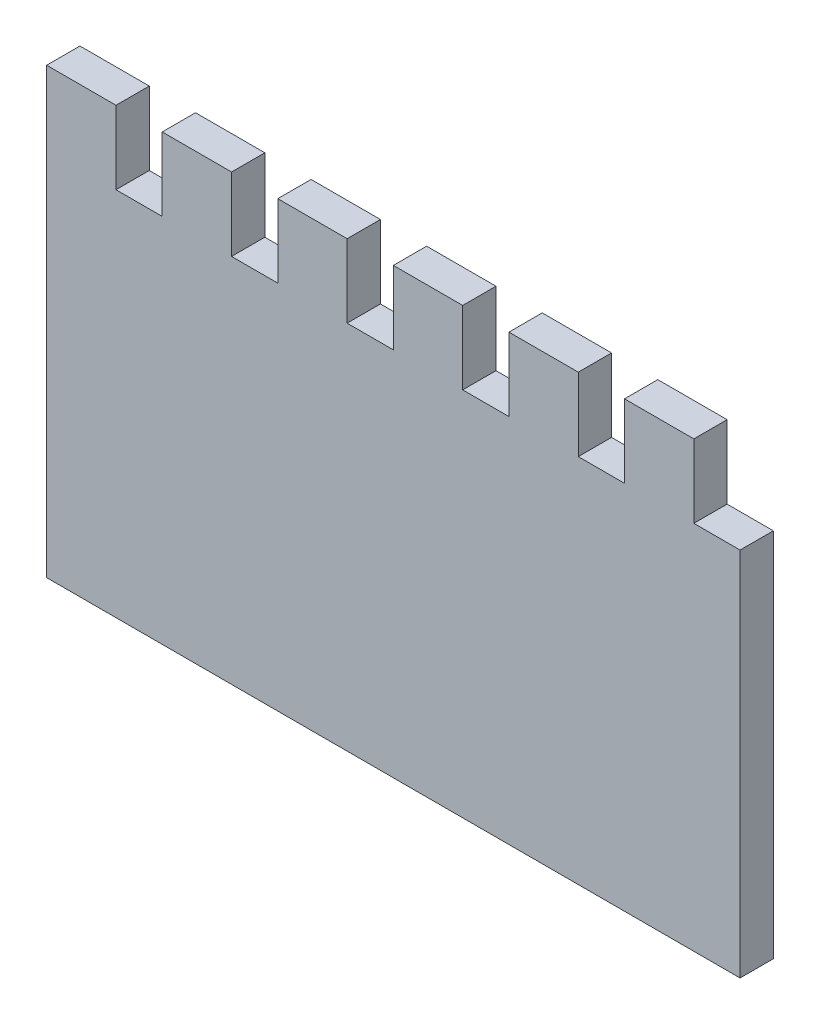
SolidWorks part; units mm, degrees
ref_plane "Front Plane" through (0, 0, 0) normal (0, 0, 1) x (1, 0, 0)
ref_plane "Top Plane" through (0, 0, 0) normal (0, 1, 0) x (1, 0, 0)
ref_plane "Right Plane" through (0, 0, 0) normal (1, 0, 0) x (0, 0, -1)
sketch "Sketch1" plane through (0, 0, 0) normal (0, 0, 1) x (1, 0, 0)
  line L1 (0, 0) -> (38100, 0)
  line L2 (0, 0) -> (0, 24384)
  line L3 (0, 24384) -> (38100, 24384)
  line L4 (38100, 0) -> (38100, 24384)
  dimension "D1" = 38100
  dimension "D2" = 24384
extrude "Boss-Extrude1" add sketch "Sketch1" along normal blind 1828.8
sketch "Sketch2" plane through (0, 0, 1828.8) normal (0, 0, 1) x (1, 0, 0)
  line L0 (0, 24384) -> (0, 20364.7506)
  line L1 (0, 24384) -> (0, 0) construction
  line L2 (0, 20364.7506) -> (3810, 20364.7506)
  line L3 (3810, 20364.7506) -> (3810, 24384)
  line L4 (38100, 24384) -> (0, 24384) construction
  line L5 (3810, 24384) -> (0, 24384)
  line L6 (6350, 24384) -> (6350, 20364.7506)
  line L7 (6350, 20364.7506) -> (10160, 20364.7506)
  line L8 (10160, 20364.7506) -> (10160, 24384)
  line L9 (10160, 24384) -> (6350, 24384)
  line L10 (11430, 24384) -> (12700, 24384)
  line L11 (16510, 24384) -> (19050, 24384)
  line L12 (16510, 24384) -> (19050, 24384)
  line L13 (6350, 24384) -> (11430, 24384)
  line L14 (19050, 24384) -> (19050, 20364.7506)
  line L15 (19050, 20364.7506) -> (22860, 20364.7506)
  line L16 (22860, 20364.7506) -> (22860, 24384)
  line L17 (22860, 24384) -> (19050, 24384)
  line L18 (25400, 24384) -> (25400, 20364.7506)
  line L19 (25400, 20364.7506) -> (29210, 20364.7506)
  line L20 (29210, 20364.7506) -> (29210, 24384)
  line L21 (29210, 24384) -> (25400, 24384)
  line L22 (31750, 24384) -> (31750, 20364.7506)
  line L23 (31750, 24384) -> (35560, 24384)
  line L24 (38100, 20364.7506) -> (38100, 24384)
  line L25 (3810, 20364.7506) -> (6350, 20364.7506)
  line L26 (3810, 24384) -> (6350, 24384)
  line L27 (10160, 24384) -> (11430, 24384)
  line L28 (11430, 24384) -> (10160, 24384)
  line L29 (16510, 24384) -> (19050, 24384)
  line L30 (22860, 24384) -> (25400, 24384)
  line L31 (10160, 24384) -> (12700, 24384)
  line L32 (16510, 24384) -> (19050, 24384)
  line L33 (12700, 24384) -> (16510, 24384)
  line L34 (12700, 24384) -> (12700, 20364.7506)
  line L35 (12700, 20364.7506) -> (16510, 20364.7506)
  line L36 (16510, 24384) -> (16510, 20364.7506)
  line L37 (6350, 24384) -> (12700, 24384)
  line L38 (22860, 24384) -> (25400, 24384)
  line L39 (12700, 20364.7506) -> (10160, 20364.7506)
  line L40 (22860, 24384) -> (25400, 24384)
  line L41 (29210, 24384) -> (31750, 24384)
  line L42 (35560, 20364.7506) -> (35560, 24384)
  line L43 (31750, 20364.7506) -> (35560, 20364.7506)
  line L44 (16510, 20364.7506) -> (19050, 20364.7506)
  line L45 (19050, 24384) -> (16510, 24384)
  line L46 (22860, 24384) -> (25400, 24384)
  line L47 (25400, 20364.7506) -> (22860, 20364.7506)
  line L48 (29210, 20364.7506) -> (31750, 20364.7506)
  line L49 (31750, 24384) -> (29210, 24384)
  line L50 (35560, 24384) -> (38100, 24384)
  line L51 (38100, 20364.7506) -> (35560, 20364.7506)
  line L52 (38100, 20364.7506) -> (38100, 24384)
  line M3 (38100, 0) -> (38100, 24384)
  line M4 (38100, 24384) -> (0, 24384)
  dimension "D1" = 2540
  dimension "D2" = 2540
  dimension "D3" = 2540
  dimension "D5" = 3810
extrude "Cut-Extrude2" cut sketch "Sketch2" against normal blind 1828.8 contours L3 L25 L6 M4 | L39 L34 L8 M4 | L36 L44 L14 M4 | L47 L18 L16 M4 | L20 L48 L22 M4 | L51 L42 M3 M4
sketch "Sketch3" plane through (0, 0, 1828.8) normal (0, 0, 1) x (1, 0, 0)
  line L0 (0, 19685.709) -> (38100, 19685.709)
  line L1 (0, 24384) -> (0, 0) construction
  line L2 (38100, 0) -> (38100, 20364.7506) construction
  line L3 (38100, 19685.709) -> (38100, 18771.309)
  line L4 (38100, 18771.309) -> (0, 18771.309)
  line L5 (0, 18771.309) -> (0, 19685.709)
  dimension "D1" = 914.4
